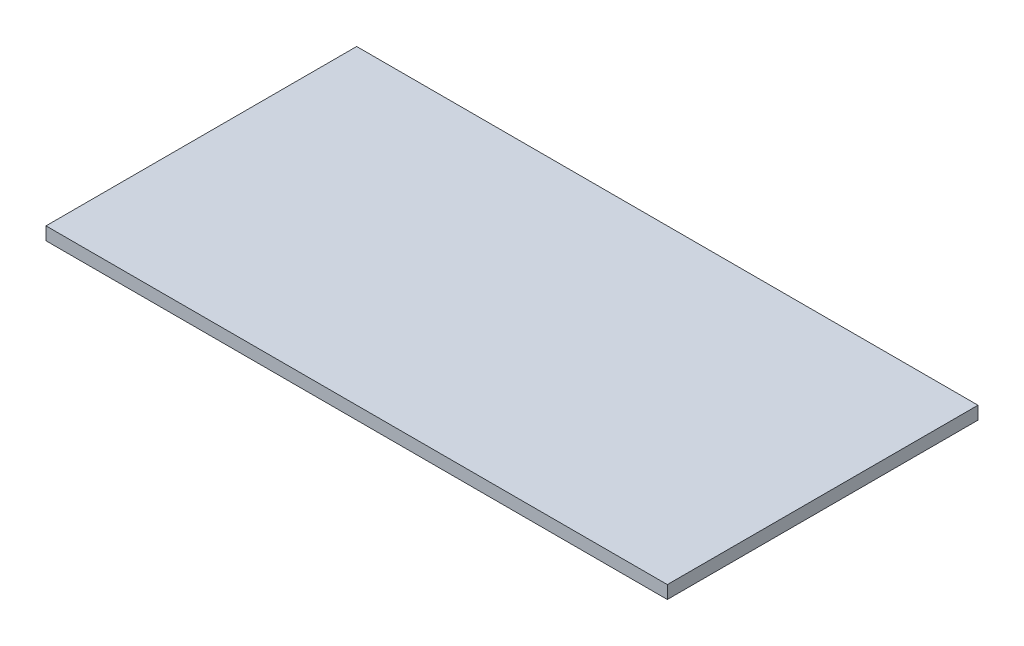
SolidWorks part; units mm, degrees
ref_plane "Front Plane" through (0, 0, 0) normal (0, 0, 1) x (1, 0, 0)
ref_plane "Top Plane" through (0, 0, 0) normal (0, 1, 0) x (1, 0, 0)
ref_plane "Right Plane" through (0, 0, 0) normal (1, 0, 0) x (0, 0, -1)
sketch "Sketch1" plane through (0, 0, 0) normal (0, 1, 0) x (1, 0, 0)
  line L1 (0, 0) -> (609.6, 0)
  line L2 (0, 0) -> (0, 304.8)
  line L3 (0, 304.8) -> (609.6, 304.8)
  line L4 (609.6, 0) -> (609.6, 304.8)
  dimension "D1" = 304.8
  dimension "D2" = 609.6
extrude "Boss-Extrude1" add sketch "Sketch1" along normal blind 12.7
